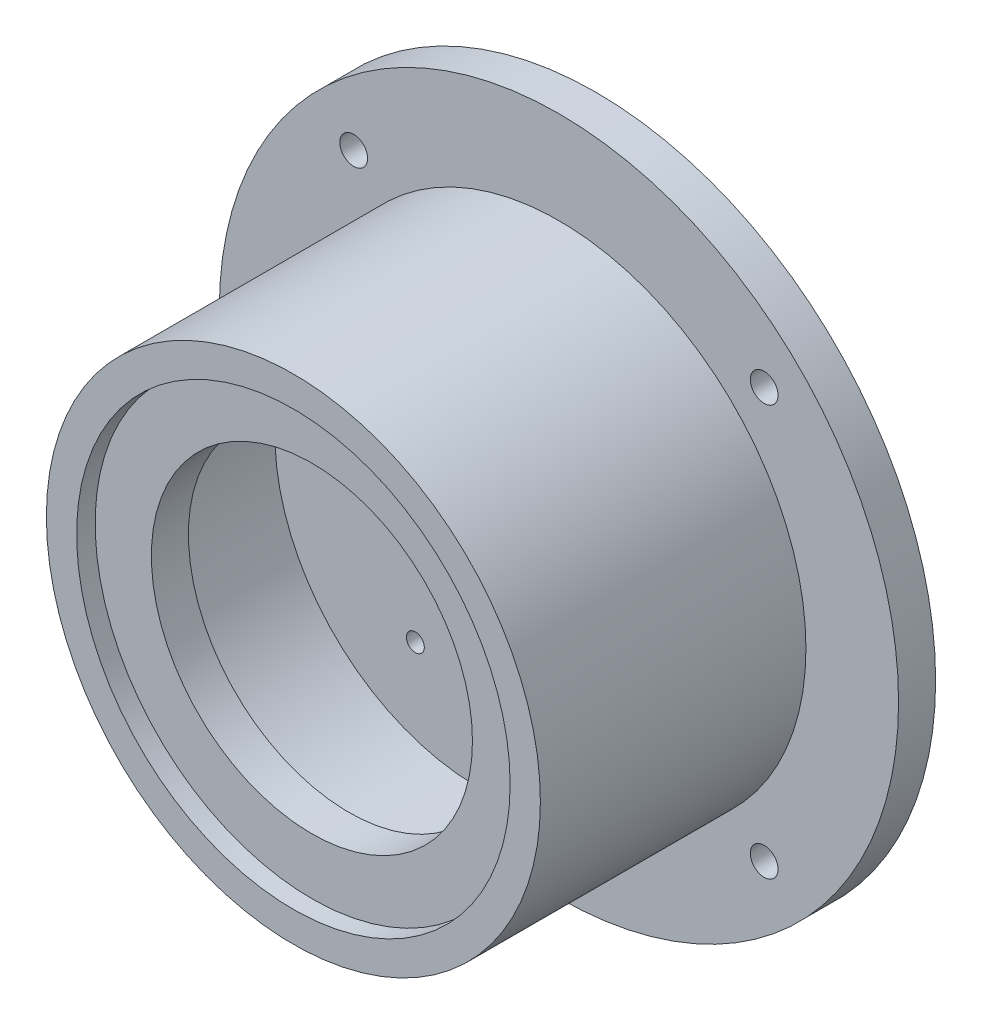
SolidWorks part; units mm, degrees
material "Aleación 6061"
ref_plane "Alzado" through (0, 0, 0) normal (0, 0, 1) x (1, 0, 0)
ref_plane "Planta" through (0, 0, 0) normal (0, 1, 0) x (1, 0, 0)
ref_plane "Vista lateral" through (0, 0, 0) normal (1, 0, 0) x (0, 0, -1)
sketch "Sk_Brida" plane through (0, 0, 0) normal (0, 0, 1) x (1, 0, 0)
  circle A0 centre (0, 0) radius 55
  dimension "D1" = 110
extrude "Brida" add sketch "Sk_Brida" along normal blind 6 from offset 10
sketch "Sk_Tubo" plane through (0, 0, 0) normal (0, 0, 1) x (1, 0, 0)
  circle A0 centre (0, 0) radius 40
  circle A1 centre (0, 0) radius 33
  dimension "D1" = 80
  dimension "D2" = 66
extrude "Tubo" add sketch "Sk_Tubo" along normal blind 34 from offset 16
sketch "Sk_Aro_rodamiento" plane through (0, 0, 0) normal (0, 0, 1) x (1, 0, 0)
  circle A0 centre (0, 0) radius 40
  circle A1 centre (0, 0) radius 26
  dimension "D1" = 80
  dimension "D2" = 52
extrude "Aro_rodamiento" add sketch "Sk_Aro_rodamiento" along normal blind 6 from offset 50
sketch "Sk_Asiento_arandela_alojamiento_51110" plane through (0, 0, 0) normal (0, 0, 1) x (1, 0, 0)
  circle A0 centre (0, 0) radius 40
  circle A1 centre (0, 0) radius 35.1
  dimension "D1" = 80
  dimension "D2" = 70.2
extrude "Asiento_arandela_alojamiento_51110" add sketch "Sk_Asiento_arandela_alojamiento_51110" along normal blind 3 from offset 56
sketch "Sk_Placa_motor" plane through (0, 0, 0) normal (0, 0, 1) x (1, 0, 0)
  circle A0 centre (0, 0) radius 33
  dimension "D1" = 66
extrude "Placa_motor" add sketch "Sk_Placa_motor" along normal blind 6 from offset 23
sketch "Sk_Hueco_brida" plane through (0, 0, 0) normal (0, 0, 1) x (1, 0, 0)
  circle A0 centre (0, 0) radius 28
  dimension "D1" = 56
extrude "Hueco_brida" cut sketch "Sk_Hueco_brida" along normal blind 13 from offset 10
sketch "Sk_Centro_motor" plane through (0, 0, 0) normal (0, 0, 1) x (1, 0, 0)
  circle A0 centre (0, 0) radius 8
  dimension "D1" = 16
extrude "Centro_motor" cut sketch "Sk_Centro_motor" along normal blind 6 from offset 23
sketch "Sk_Pasantes_M2-5_motor" plane through (0, 0, 0) normal (0, 0, 1) x (1, 0, 0)
  circle A0 centre (20.5, 0) radius 1.45
  circle A1 centre (10.25, 17.7535) radius 1.45
  circle A2 centre (-10.25, 17.7535) radius 1.45
  circle A3 centre (-20.5, 0) radius 1.45
  circle A4 centre (-10.25, -17.7535) radius 1.45
  circle A5 centre (10.25, -17.7535) radius 1.45
  dimension "D1" = 2.9
  dimension "D3" = 2.9
  dimension "D6" = 2.9
  dimension "D9" = 2.9
  dimension "D11" = 2.9
  dimension "D14" = 2.9
  dimension "D2" = 20.5
  dimension "D4" = 10.25
  dimension "D5" = 17.7535
  dimension "D7" = 10.25
  dimension "D8" = 17.7535
  dimension "D10" = 20.5
  dimension "D12" = 10.25
  dimension "D13" = 17.7535
  dimension "D15" = 10.25
  dimension "D16" = 17.7535
extrude "Pasantes_M2-5_motor" cut sketch "Sk_Pasantes_M2-5_motor" along normal blind 6 from offset 23
sketch "Sk_Pasantes_M4_brida" plane through (0, 0, 0) normal (0, 0, 1) x (1, 0, 0)
  circle A0 centre (33.234, 33.234) radius 2.25
  circle A1 centre (-33.234, 33.234) radius 2.25
  circle A2 centre (-33.234, -33.234) radius 2.25
  circle A3 centre (33.234, -33.234) radius 2.25
  dimension "D1" = 4.5
  dimension "D4" = 4.5
  dimension "D7" = 4.5
  dimension "D10" = 4.5
  dimension "D2" = 33.234
  dimension "D3" = 33.234
  dimension "D5" = 33.234
  dimension "D6" = 33.234
  dimension "D8" = 33.234
  dimension "D9" = 33.234
  dimension "D11" = 33.234
  dimension "D12" = 33.234
extrude "Pasantes_M4_brida" cut sketch "Sk_Pasantes_M4_brida" along normal blind 6 from offset 10
